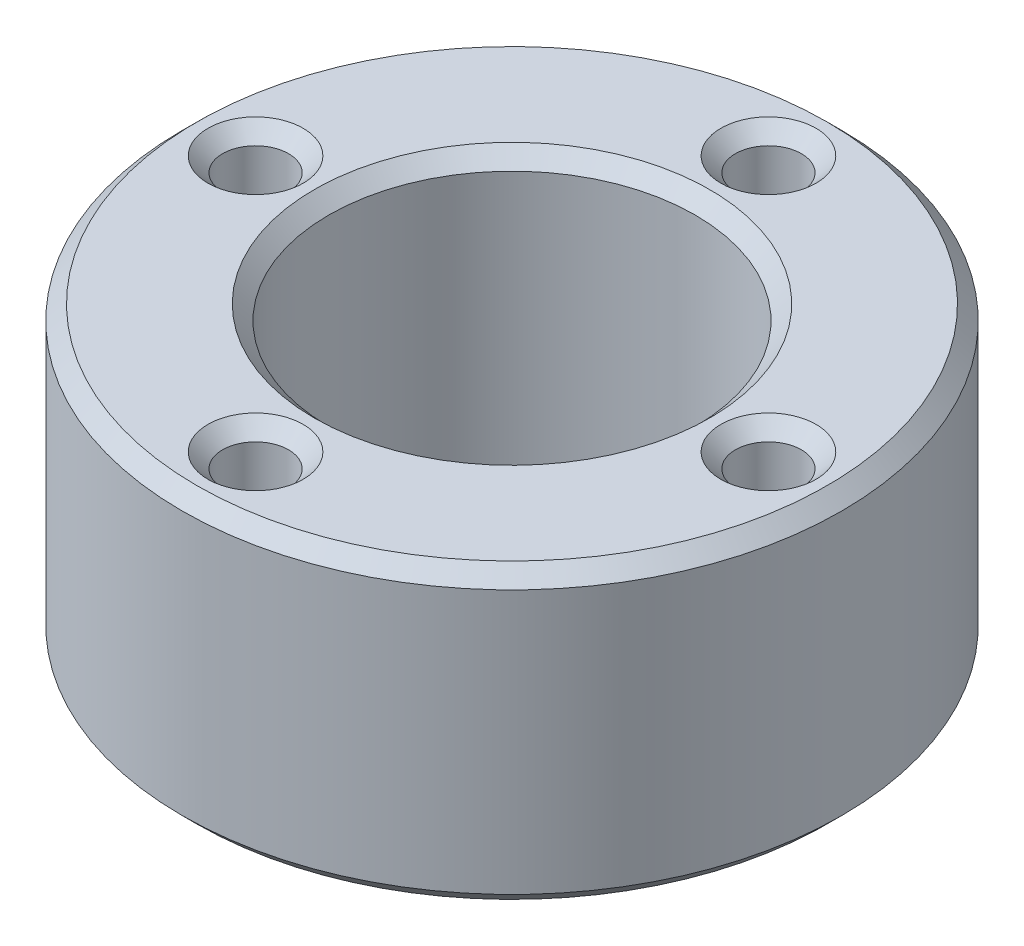
SolidWorks part; units mm, degrees
material "ABS"
ref_plane "Front Plane" through (0, 0, 0) normal (0, 0, 1) x (1, 0, 0)
ref_plane "Top Plane" through (0, 0, 0) normal (0, 1, 0) x (1, 0, 0)
ref_plane "Right Plane" through (0, 0, 0) normal (1, 0, 0) x (0, 0, -1)
sketch "Sketch1" plane through (0, 0, 0) normal (0, 1, 0) x (1, 0, 0)
  line L0 (-30.5169, 0) -> (34.0499, 0) construction
  circle A4 centre (0, 0) radius 22.5
  circle A5 centre (-17.5, 0) radius 2.25
  circle A6 centre (0, 17.5) radius 2.25
  circle A7 centre (17.5, 0) radius 2.25
  circle A8 centre (0, -17.5) radius 2.25
  circle A9 centre (0, 0) radius 12.5
  point P15 (0, 0)
  dimension "D1" = 45
  dimension "D2" = 4.5
  dimension "D7" = 25
  dimension "D3" = 17.5
  dimension "D4" = 4
  dimension "D5" = 17.5
  dimension "D6" = 17.5
extrude "Boss-Extrude1" add sketch "Sketch1" along normal blind 20
chamfer "Chamfer1" distance 1 angle 45 12 edges at (0, 0, 19.75) (17.5, 0, 2.25) (0, 0, -15.25) (0, 0, 12.5) (-17.5, 0, 2.25) (0, 0, 22.5) (0, 20, 19.75) (0, 20, -15.25) (-17.5, 20, 2.25) (0, 20, 22.5) (0, 20, 12.5) (17.5, 20, 2.25)
